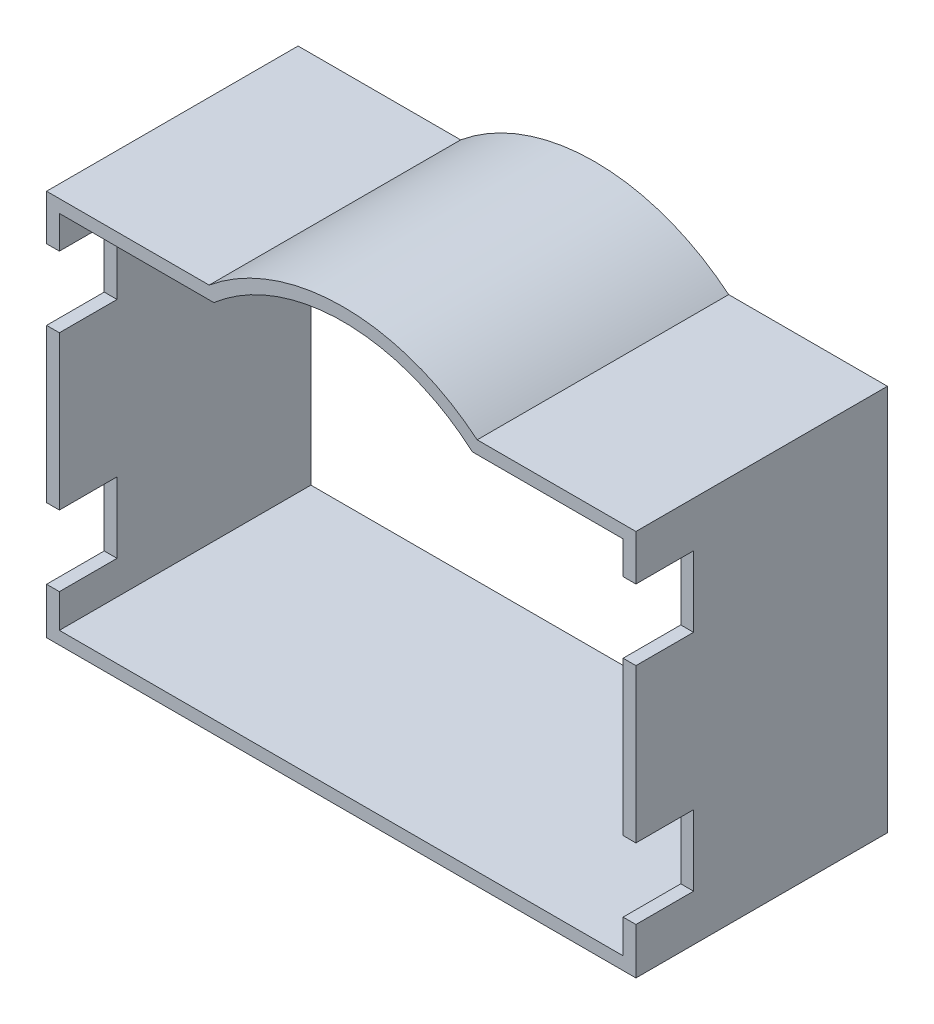
SolidWorks part; units mm, degrees
material "Custom Plastic"
ref_plane "X-Y Datum" through (0, 0, 0) normal (0, 0, 1) x (1, 0, 0)
ref_plane "X-Z Datum" through (0, 0, 0) normal (0, 1, 0) x (1, 0, 0)
ref_plane "Y-Z Datum" through (0, 0, 0) normal (1, 0, 0) x (0, 0, -1)
sketch "Sketch2" plane through (0, 0, 0) normal (0, 0, 1) x (1, 0, 0)
  line L10 (20.2253, 68.844) -> (49.6094, 68.844) construction
  line L11 (-60.6216, -1.2152) -> (49.6094, -1.2152) construction
  line L12 (-60.6216, -1.2152) -> (-60.6216, 68.844) construction
  line L13 (-60.6216, 68.844) -> (-30.4754, 68.844) construction
  line L14 (49.6094, -1.2152) -> (49.6094, 68.844) construction
  line L15 (20.511, 69.606) -> (50.3714, 69.606)
  line L16 (50.3714, -1.9772) -> (50.3714, 69.606)
  line L17 (-61.3836, -1.9772) -> (50.3714, -1.9772)
  line L18 (-61.3836, -1.9772) -> (-61.3836, 69.606)
  line L19 (-61.3836, 69.606) -> (-30.7611, 69.606)
  arc A3 (-30.4754, 68.844) -> (20.2253, 68.844) centre (-5.1251, 40.0051) cw construction
  arc A4 (-30.7611, 69.606) -> (20.511, 69.606) centre (-5.1251, 40.0051) cw
  point P7 (5.0078, 15.3711)
  point P11 (4.8071, 85.4303)
  dimension "D1" = 0.762
extrude "Boss-Extrude2" add sketch "Sketch2" along normal blind 49.8602
shell "Shell2" thickness 2.54
sketch "Sketch3" plane through (0, 0, 49.8602) normal (0, 0, 1) x (1, 0, 0)
  line L0 (-63.9236, 72.146) -> (52.9114, 72.146) construction
  line L1 (-63.9236, 72.146) -> (-63.9236, -4.5172) construction
  line L2 (-63.9236, -4.5172) -> (52.9114, -4.5172) construction
  line L3 (52.9114, 72.146) -> (52.9114, -4.5172) construction
  line L4 (52.9114, 63.119) -> (61.0484, 63.119)
  line L5 (52.9114, 63.119) -> (52.9114, 49.119)
  line L6 (52.9114, 49.119) -> (61.0484, 49.119)
  line L7 (61.0484, 63.119) -> (61.0484, 49.119)
  line L8 (52.9114, 4.669) -> (61.0484, 4.669)
  line L9 (52.9114, 4.669) -> (52.9114, 18.669)
  line L10 (52.9114, 18.669) -> (61.0484, 18.669)
  line L11 (61.0484, 4.669) -> (61.0484, 18.669)
  line L12 (-63.9236, 63.119) -> (-71.5316, 63.119)
  line L13 (-63.9236, 63.119) -> (-63.9236, 49.119)
  line L14 (-63.9236, 49.119) -> (-71.5316, 49.119)
  line L15 (-71.5316, 63.119) -> (-71.5316, 49.119)
  line L16 (-63.9236, 18.669) -> (-71.5316, 18.669)
  line L17 (-63.9236, 18.669) -> (-63.9236, 4.669)
  line L18 (-63.9236, 4.669) -> (-71.5316, 4.669)
  line L19 (-71.5316, 18.669) -> (-71.5316, 4.669)
  circle A0 centre (-66.3316, 56.119) radius 2.58
  circle A1 centre (-66.3316, 11.669) radius 2.58
  circle A2 centre (55.8484, 56.119) radius 2.58
  circle A3 centre (55.8484, 11.669) radius 2.58
sketch "Sketch4" plane through (0, 0, 49.8602) normal (0, 0, 1) x (1, 0, 0)
  line L0 (-61.3836, 69.606) -> (-61.3836, -1.9772) construction
  line L1 (-63.9236, 63.119) -> (-61.3836, 63.119)
  line L2 (-63.9236, 63.119) -> (-63.9236, 49.1149)
  line L3 (-63.9236, 49.1149) -> (-61.3836, 49.1149)
  line L4 (-61.3836, 63.119) -> (-61.3836, 49.1149)
  line L5 (50.3714, -1.9772) -> (50.3714, 69.606) construction
  line L6 (-63.9236, 18.669) -> (-61.3836, 18.669)
  line L7 (-63.9236, 18.669) -> (-63.9236, 4.669)
  line L8 (-63.9236, 4.669) -> (-61.3836, 4.669)
  line L9 (-61.3836, 18.669) -> (-61.3836, 4.669)
  line L10 (52.9114, 63.119) -> (50.3714, 63.119)
  line L11 (52.9114, 63.119) -> (52.9114, 49.1149)
  line L12 (52.9114, 49.1149) -> (50.3714, 49.1149)
  line L13 (50.3714, 63.119) -> (50.3714, 49.1149)
  line L15 (52.9114, 18.669) -> (50.3714, 18.669)
  line L16 (52.9114, 18.669) -> (52.9114, 4.669)
  line L17 (52.9114, 4.669) -> (50.3714, 4.669)
  line L18 (50.3714, 18.669) -> (50.3714, 4.669)
extrude "Cut-Extrude1" cut sketch "Sketch4" against normal blind 11.43
